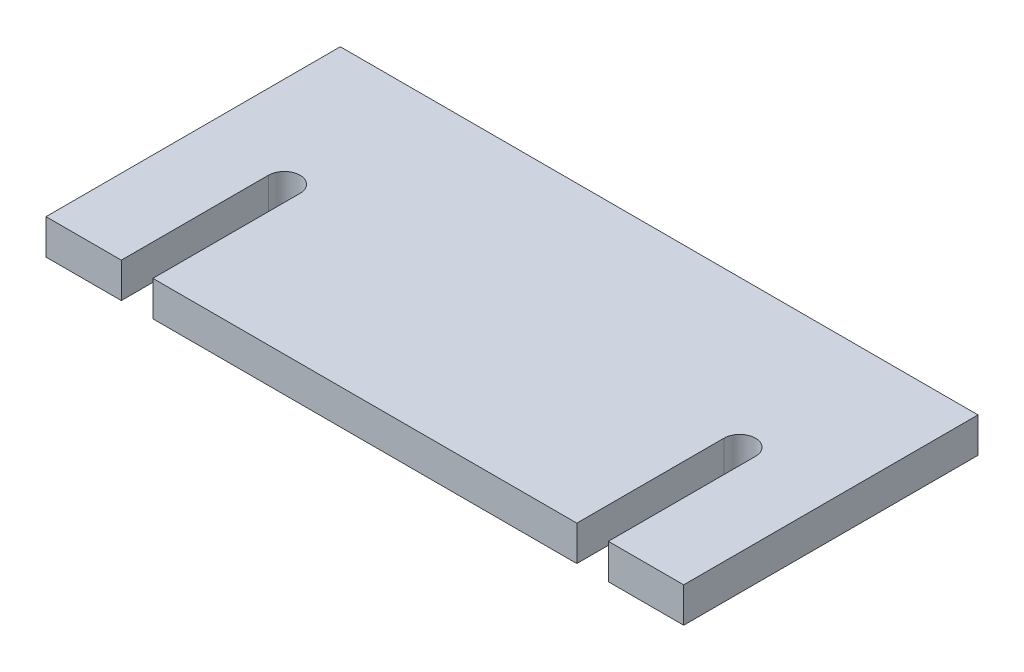
SolidWorks part; units mm, degrees
ref_plane "정면" through (0, 0, 0) normal (0, 0, 1) x (1, 0, 0)
ref_plane "윗면" through (0, 0, 0) normal (0, 1, 0) x (1, 0, 0)
ref_plane "우측면" through (0, 0, 0) normal (1, 0, 0) x (0, 0, -1)
sketch "스케치1" plane through (0, 0, 0) normal (0, 1, 0) x (1, 0, 0)
  line L1 (-45.5, -21) -> (45.5, -21)
  line L2 (-45.5, -21) -> (-45.5, 21)
  line L3 (-45.5, 21) -> (45.5, 21)
  line L4 (45.5, -21) -> (45.5, 21)
  line L5 (-45.5, -21) -> (45.5, 21) construction
  line L6 (-45.5, 21) -> (45.5, -21) construction
  point P0 (0, 0)
  dimension "D1" = 91
  dimension "D2" = 42
extrude "보스-돌출1" add sketch "스케치1" along normal blind 5
sketch "스케치2" plane through (0, 5, 0) normal (0, 1, 0) x (1, 0, 0)
  line L0 (32.5, 0) -> (32.5, -21) construction
  line L1 (-45.5, -21) -> (45.5, -21) construction
  line L2 (34.75, 0) -> (34.75, -21)
  line L3 (30.25, 0) -> (30.25, -21)
  line L4 (-32.5, 0) -> (-32.5, -21) construction
  line L5 (-30.25, 0) -> (-30.25, -21)
  line L6 (32.5, 0) -> (-32.5, 0) construction
  line L7 (-32.5, 0) -> (-45.5, 0) construction
  line L8 (-45.5, 21) -> (-45.5, -21) construction
  line L9 (32.5, 0) -> (45.5, 0) construction
  line L10 (45.5, -21) -> (45.5, 21) construction
  line L11 (-34.75, 0) -> (-34.75, -21)
  arc A0 (34.75, 0) -> (30.25, 0) centre (32.5, 0) ccw
  arc A1 (30.25, -21) -> (34.75, -21) centre (32.5, -21) ccw
  arc A2 (-30.25, 0) -> (-34.75, 0) centre (-32.5, 0) ccw
  arc A3 (-34.75, -21) -> (-30.25, -21) centre (-32.5, -21) ccw
  point P0 (32.5, -10.5)
  point P8 (-32.5, -10.5)
  dimension "D2" = 2.25
  dimension "D1" = 65
extrude "컷-돌출1" cut sketch "스케치2" against normal blind 5
